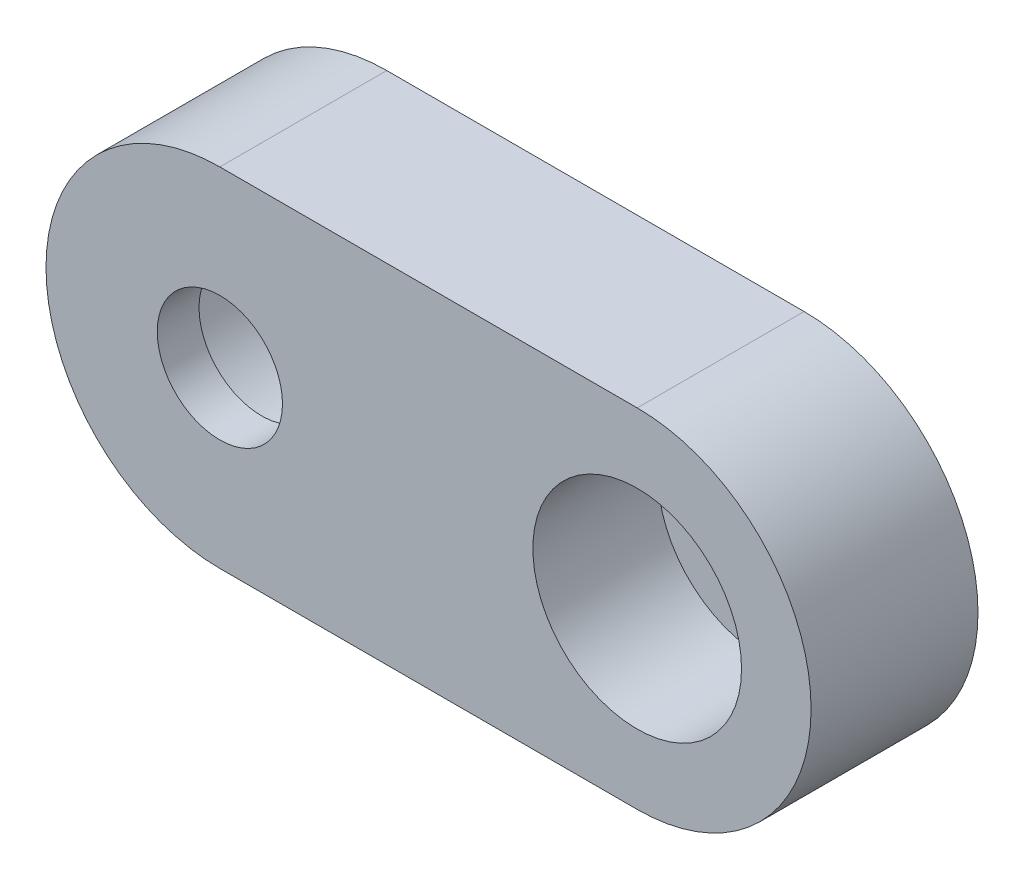
SolidWorks part; units mm, degrees
ref_plane "前视基准面" through (0, 0, 0) normal (0, 0, 1) x (1, 0, 0)
ref_plane "上视基准面" through (0, 0, 0) normal (0, 1, 0) x (1, 0, 0)
ref_plane "右视基准面" through (0, 0, 0) normal (1, 0, 0) x (0, 0, -1)
sketch "草图1" plane through (0, 0, 0) normal (0, 0, 1) x (1, 0, 0)
  line L0 (-15, 0) -> (15, 0) construction
  line L1 (-15, 12.5) -> (15, 12.5)
  line L2 (-15, -12.5) -> (15, -12.5)
  arc A0 (-15, 12.5) -> (-15, -12.5) centre (-15, 0) ccw
  arc A1 (15, -12.5) -> (15, 12.5) centre (15, 0) ccw
  point P2 (0, 0)
  dimension "D1" = 25
  dimension "D2" = 30
extrude "凸台-拉伸1" add sketch "草图1" along normal blind 12
hole_wizard "打孔尺寸(%根据)内六角圆柱头螺钉的类型1" positions "草图2" profile "草图3" counterbore size "M8" standard "GB"
sketch "草图2" plane through (0, 0, 0) normal (0, 0, -1) x (-1, 0, 0)
  point P0 (15, 0)
sketch "草图3" plane through (-15, 0, 0) normal (1, 0, 0) x (0, 1, 0)
  line L0 (0, 0) -> (0, 22.4539)
  line L1 (0, 22.4539) -> (4.5, 19.75)
  line L2 (4.5, 19.75) -> (4.5, 9)
  line L3 (4.5, 9) -> (7.5, 9)
  line L4 (7.5, 9) -> (7.5, 0)
  line L5 (7.5, 0) -> (0, 0)
  line L10 (0, 22.4539) -> (-4.5, 19.75) construction
  line L11 (0, -6.35) -> (0, 107.95) construction
  dimension "孔直径" = 9
  dimension "孔深度" = 19.75
  dimension "柱形沉头孔直径" = 15
  dimension "柱形沉头孔深度" = 9
  dimension "导头角度" = 118
hole_wizard "打孔尺寸(%根据)内六角圆柱头螺钉的类型2" positions "草图4" profile "草图5" counterbore size "M8" standard "GB"
sketch "草图4" plane through (0, 0, 12) normal (0, 0, 1) x (1, 0, 0)
  point P0 (15, 0)
sketch "草图5" plane through (15, 0, 12) normal (1, 0, 0) x (0, -1, 0)
  line L0 (0, 0) -> (0, 22.4539)
  line L1 (0, 22.4539) -> (4.5, 19.75)
  line L2 (4.5, 19.75) -> (4.5, 9)
  line L3 (4.5, 9) -> (7.5, 9)
  line L4 (7.5, 9) -> (7.5, 0)
  line L5 (7.5, 0) -> (0, 0)
  line L10 (0, 22.4539) -> (-4.5, 19.75) construction
  line L11 (0, -6.35) -> (0, 107.95) construction
  dimension "孔直径" = 9
  dimension "孔深度" = 19.75
  dimension "柱形沉头孔直径" = 15
  dimension "柱形沉头孔深度" = 9
  dimension "导头角度" = 118
